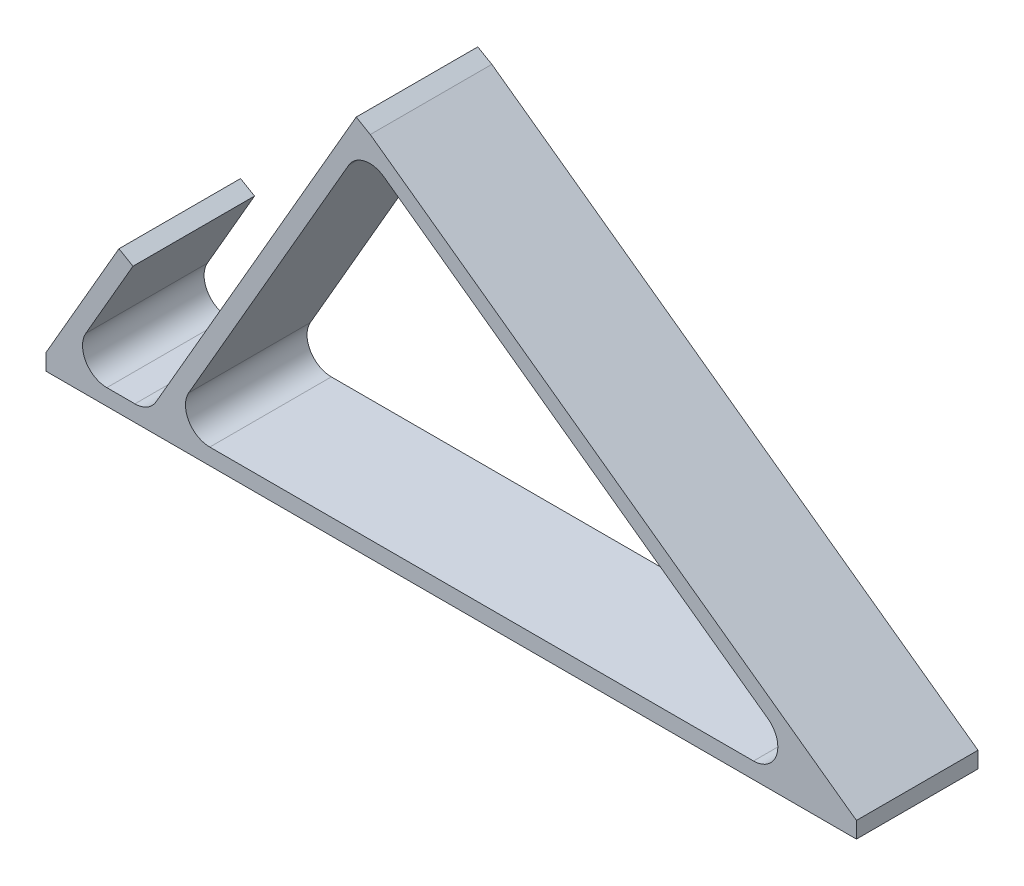
SolidWorks part; units mm, degrees
ref_plane "Front Plane" through (0, 0, 0) normal (0, 0, 1) x (1, 0, 0)
ref_plane "Top Plane" through (0, 0, 0) normal (0, 1, 0) x (1, 0, 0)
ref_plane "Right Plane" through (0, 0, 0) normal (1, 0, 0) x (0, 0, -1)
sketch "Sketch1" plane through (0, 0, 0) normal (0, 0, 1) x (1, 0, 0)
  line L0 (0, 0) -> (100, 0)
  line L1 (100, 0) -> (100, 2)
  line L2 (87.3009, 2) -> (20.2073, 2)
  line L3 (0, 2) -> (0, 0)
  line L4 (0, 2) -> (9, 17.5885)
  line L5 (10.7321, 16.5885) -> (9, 17.5885)
  line L6 (37.3452, 40.6838) -> (17.6092, 6.5)
  line L7 (4.9075, 6.5) -> (10.7321, 16.5885)
  line L8 (38.2791, 46.3013) -> (13.5677, 3.5)
  line L9 (38.2791, 46.3013) -> (40.0111, 45.3013)
  line L10 (32.0894, 35.5805) -> (13.2791, 3) construction
  line L11 (1.7321, 1) -> (10.7321, 16.5885) construction
  line L12 (9.1616, 17.8683) -> (40.0111, 45.3013) construction
  line L13 (10.7321, 16.5885) -> (32.0894, 35.5805) construction
  line L14 (0, 2) -> (9.1616, 17.8683) construction
  line L15 (38.2791, 46.3013) -> (13.2791, 3) construction
  line L16 (7.5056, 2) -> (10.9697, 2)
  line L17 (40.0111, 45.3013) -> (100, 2)
  line L18 (41.6991, 41.6163) -> (89.0567, 7.4325)
  line L20 (38.8406, 43.6796) -> (98.8294, 0.3783) construction
  line L21 (40.0111, 45.3013) -> (15.0111, 2) construction
  arc A0 (89.0567, 7.4325) -> (87.3009, 2) centre (87.3009, 5) cw
  arc A1 (37.3452, 40.6838) -> (41.6991, 41.6163) centre (39.9433, 39.1838) cw
  arc A2 (17.6092, 6.5) -> (20.2073, 2) centre (20.2073, 5) ccw
  arc A3 (4.9075, 6.5) -> (7.5056, 2) centre (7.5056, 5) ccw
  arc A4 (13.5677, 3.5) -> (10.9697, 2) centre (10.9697, 5) cw
  point P30 (2.3094, 2)
  point P33 (0, 0)
  dimension "D10" = 3
  dimension "D1" = 2
  dimension "D2" = 100
  dimension "D3" = 13
  dimension "D4" = 18
  dimension "D6" = 60
  dimension "D5" = 2
  dimension "D8" = 2
  dimension "D9" = 2
extrude "Boss-Extrude1" add sketch "Sketch1" along normal blind 15
